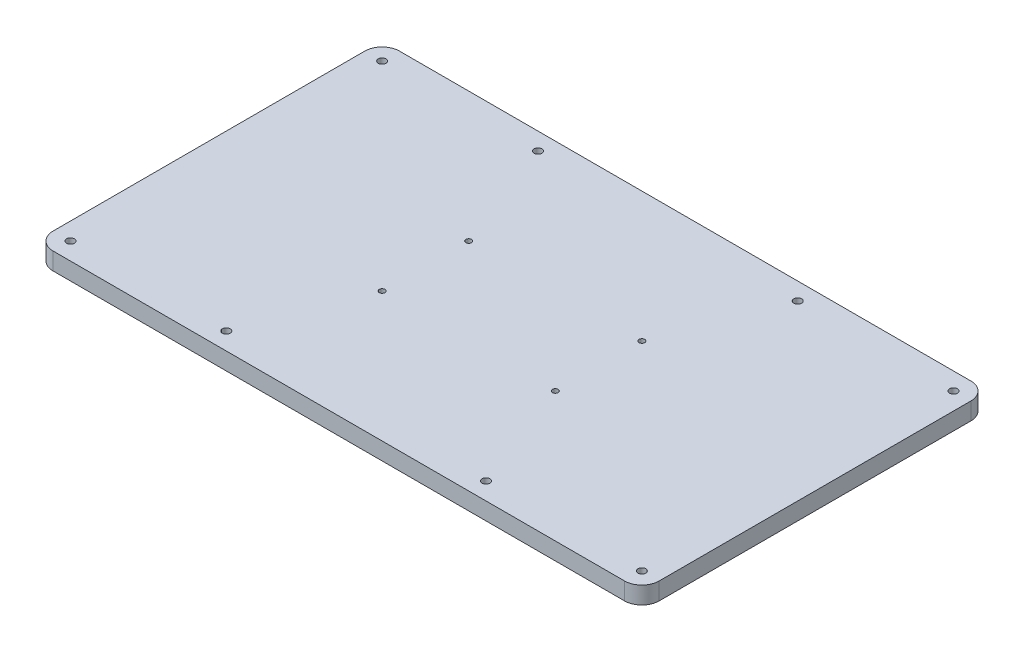
SolidWorks part; units mm, degrees
material "3.1355 (EN-AW 2024)"
ref_plane "Спереди" through (0, 0, 0) normal (0, 0, 1) x (1, 0, 0)
ref_plane "Сверху" through (0, 0, 0) normal (0, 1, 0) x (1, 0, 0)
ref_plane "Справа" through (0, 0, 0) normal (1, 0, 0) x (0, 0, -1)
sketch "Эскиз1" plane through (0, 0, 0) normal (0, 1, 0) x (1, 0, 0)
  line L1 (0, 0) -> (350, 0)
  line L2 (0, 0) -> (0, 200)
  line L3 (0, 200) -> (350, 200)
  line L4 (350, 0) -> (350, 200)
  dimension "D1" = 350
  dimension "D2" = 200
extrude "Бобышка-Вытянуть1" add sketch "Эскиз1" along normal blind 10
sketch "Эскиз7" plane through (0, 10, 0) normal (0, 1, 0) x (1, 0, 0)
  line L0 (0, 100) -> (350, 100) construction
  line L1 (125, 75) -> (225, 75)
  line L2 (125, 75) -> (125, 125)
  line L3 (125, 125) -> (225, 125)
  line L4 (225, 75) -> (225, 125)
  line L5 (0, 200) -> (0, 0) construction
  line L6 (350, 0) -> (350, 200) construction
  line L7 (175, 0) -> (175, 200) construction
  line L8 (0, 0) -> (350, 0) construction
  line L9 (350, 200) -> (0, 200) construction
  line L10 (100, 0) -> (100, 200) construction
  line L11 (10, 10) -> (340, 10)
  line L12 (10, 10) -> (10, 190)
  line L13 (10, 190) -> (340, 190)
  line L14 (340, 10) -> (340, 190)
  line L15 (10, 10) -> (340, 190) construction
  line L16 (10, 190) -> (340, 10) construction
  line L17 (250, 0) -> (250, 200) construction
  point P16 (125, 100)
  point P17 (175, 75)
  point P18 (175, 100)
  point P27 (100, 10)
  point P28 (100, 190)
  point P29 (250, 10)
  point P30 (250, 190)
  dimension "D1" = 100
  dimension "D2" = 50
  dimension "D3" = 10
  dimension "D4" = 10
  dimension "D5" = 90
  dimension "D6" = 90
hole_wizard "Отверстие обработанное метчиком M4x0.7" positions "Эскиз4" profile "Эскиз5" tap size "M4x0.7" standard "Ansi Metric" end condition through all
sketch "Эскиз4" plane through (134.2448, 10, -121.1257) normal (0, 1, 0) x (0, 0, -1)
  point P0 (-46.1257, 9.2448)
  point P3 (3.8743, 9.2448)
  point P6 (3.8743, -90.7552)
  point P9 (-46.1257, -90.7552)
cosmetic thread "Отверстие резьбы1" parameters "D2"=4
cosmetic thread "Отверстие резьбы2" parameters "D2"=4
cosmetic thread "Отверстие резьбы3" parameters "D2"=4
cosmetic thread "Отверстие резьбы4" parameters "D2"=4
sketch "Эскиз5" plane through (125, 10, -75) normal (1, 0, 0) x (0, 0, 1)
  line L0 (0, 0) -> (0, 10)
  line L1 (0, 10) -> (1.65, 10)
  line L2 (1.65, 10) -> (1.65, 0)
  line L5 (1.65, 0) -> (0, 0)
  line L11 (0, -6.35) -> (0, 107.95) construction
  dimension "Диаметр проходного сверла" = 3.3
  dimension "Глубина проходного сверла" = 10
hole_wizard "Отверстие с зазором M42" positions "Эскиз9" profile "Эскиз8" hole size "M4" standard "Ansi Metric" end condition through all
sketch "Эскиз9" plane through (0, 10, 0) normal (0, 1, 0) x (1, 0, 0)
  point P0 (10, 10)
  point P2 (100, 10)
  point P4 (100, 190)
  point P7 (10, 190)
  point P10 (250, 190)
  point P13 (340, 190)
  point P16 (340, 10)
  point P19 (250, 10)
sketch "Эскиз8" plane through (10, 10, -10) normal (1, 0, 0) x (0, 0, 1)
  line L0 (0, 0) -> (0, 10)
  line L1 (0, 10) -> (2.25, 10)
  line L2 (2.25, 10) -> (2.25, 0)
  line L5 (2.25, 0) -> (0, 0)
  line L11 (0, -6.35) -> (0, 107.95) construction
  dimension "Диаметр сквозного отверстия" = 4.5
  dimension "Глубина сквозного отверстия" = 10
fillet "Скругление1" radius 10 4 edges at (350, 5, 0) (350, 5, -200) (0, 5, -200) (0, 5, 0)
